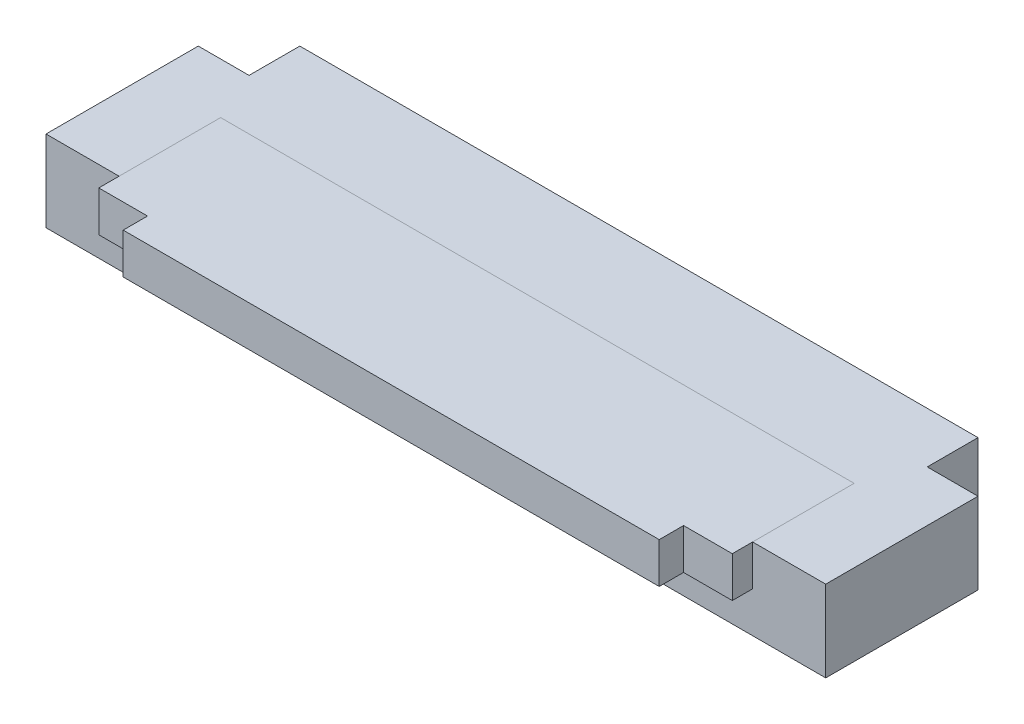
SolidWorks part; units mm, degrees
ref_plane "Front Plane" through (0, 0, 0) normal (0, 0, 1) x (1, 0, 0)
ref_plane "Top Plane" through (0, 0, 0) normal (0, 1, 0) x (1, 0, 0)
ref_plane "Right Plane" through (0, 0, 0) normal (1, 0, 0) x (0, 0, -1)
ref_plane "Plane2" through (0, 1, 0) normal (0, 1, 0) x (-1, 0, 0)
sketch "Sketch8" plane through (0, 1, 0) normal (0, 1, 0) x (-1, 0, 0)
  line L0 (-3.9, 1.5) -> (-3.9, 0)
  line L1 (-3.9, 0) -> (3.9, 0)
  line L2 (3.9, 0) -> (3.9, 1.5)
  line L3 (3.9, 1.5) -> (3.3, 1.5)
  line L4 (3.3, 1.5) -> (3.3, 1.8)
  line L5 (3.3, 1.8) -> (-3.3, 1.8)
  line L6 (-3.3, 1.8) -> (-3.3, 1.5)
  line L7 (-3.3, 1.5) -> (-3.9, 1.5)
extrude "Boss-Extrude2" add sketch "Sketch8" against normal blind 0.5 separate body
sketch "Sketch9" plane through (0, 1, 0) normal (0, 1, 0) x (-1, 0, 0)
  line L0 (4.8, 1.25) -> (-4.8, 1.25)
  line L1 (-4.8, 1.25) -> (-4.8, -1.25)
  line L2 (-4.8, -1.25) -> (4.8, -1.25)
  line L3 (4.8, -1.25) -> (4.8, 1.25)
extrude "Boss-Extrude3" add sketch "Sketch9" against normal blind 1 separate body
sketch "Sketch10" plane through (0, 0, 0) normal (0, -1, 0) x (1, 0, 0)
  line L0 (4.8, -0.625) -> (4.175, -0.625)
  line L1 (4.175, -0.625) -> (4.175, -1.25)
  line L2 (4.175, -1.25) -> (4.8, -1.25)
  line L3 (4.8, -1.25) -> (4.8, -0.625)
extrude "Cut-Extrude4" cut sketch "Sketch10" against normal through all
sketch "Sketch11" plane through (0, 0, 0) normal (0, -1, 0) x (1, 0, 0)
  line L0 (-4.175, -1.25) -> (-4.175, -0.625)
  line L1 (-4.175, -0.625) -> (-4.8, -0.625)
  line L2 (-4.8, -0.625) -> (-4.8, -1.25)
  line L3 (-4.8, -1.25) -> (-4.175, -1.25)
extrude "Cut-Extrude5" cut sketch "Sketch11" against normal through all
sketch "Sketch12" plane through (0, 1, 0) normal (0, 1, 0) x (-1, 0, 0)
  line L0 (-3.9, 1.25) -> (-3.9, 0)
  line L1 (-3.9, 0) -> (3.9, 0)
  line L2 (3.9, 0) -> (3.9, 1.25)
  line L3 (3.9, 1.25) -> (-3.9, 1.25)
extrude "Cut-Extrude6" cut sketch "Sketch12" against normal blind 0.5
